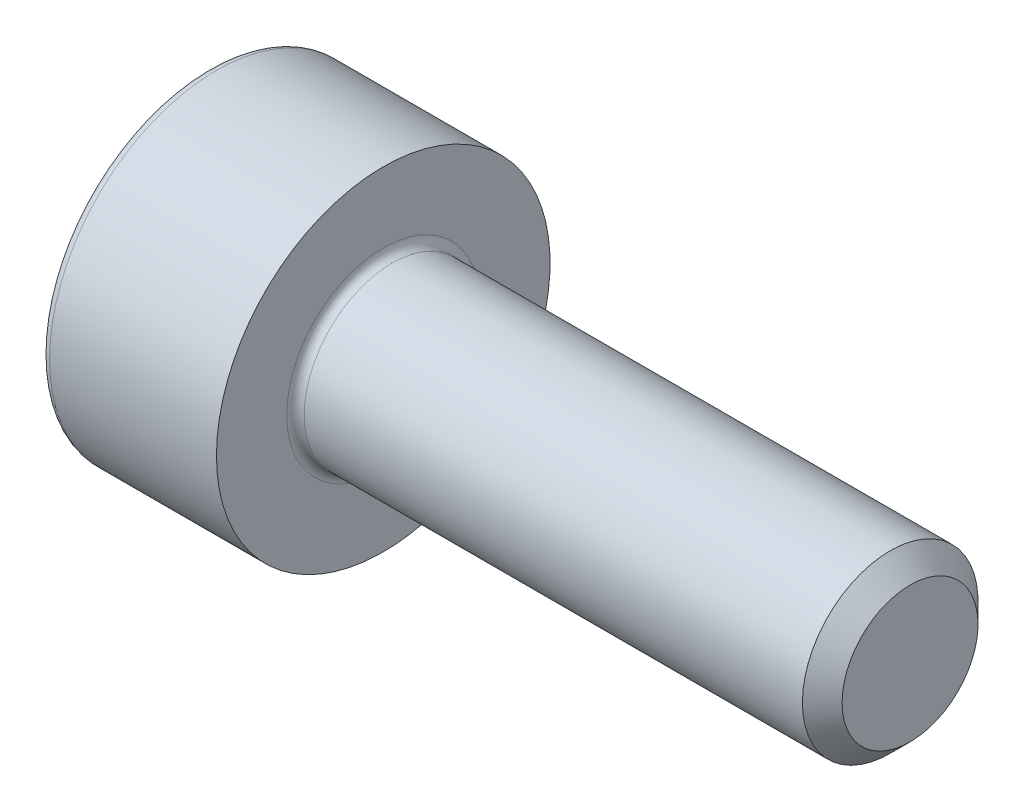
SolidWorks part; units mm, degrees
ref_plane "Plane1" through (0, 0, 0) normal (0, 0, 1) x (1, 0, 0)
ref_plane "Plane2" through (0, 0, 0) normal (0, 1, 0) x (1, 0, 0)
ref_plane "Plane3" through (0, 0, 0) normal (1, 0, 0) x (0, 0, -1)
sketch "BodySke" plane through (0, 0, 0) normal (0, 0, 1) x (1, 0, 0)
  line L0 (0, 0) -> (0, 1.9)
  line L1 (0, 1.9) -> (2, 1.9)
  line L2 (2, 1.9) -> (2, 1)
  line L3 (2, 1) -> (7.774, 1)
  line L4 (8, 0.774) -> (8, 0)
  line L5 (8, 0) -> (0, 0)
  line L6 (-31.75, 0) -> (127, 0) construction
  line L8 (8, 0.774) -> (7.774, 1)
  line L10 (8, -0.774) -> (7.774, -1) construction
  line L11 (2.4, 9.525) -> (2.4, 3.175) construction
  line L12 (2, 9.525) -> (2, 3.175) construction
  line L13 (-52, 9.525) -> (-52, 3.175) construction
  dimension "Diameter" = 2
  dimension "Head_ht" = 2
  dimension "Length" = 6
  dimension "Body_ch_ang" = 45
  dimension "Head_dia" = 3.8
  dimension "Minor_dia" = 1.548
  dimension "Advance" = 0.4
  dimension "Thread_nom" = 6
  dimension "Thread_length" = 60
revolve "Base-Revolve" add sketch "BodySke"
cosmetic thread "ThreadCosmetic" [suppressed]
fillet "Fillet1" radius 0.1 1 edges at (2, 0, 1)
fillet "Fillet2" radius 0.1 1 edges at (0, 0, 1.9)
sketch "Sketch2" plane through (0, 0, 0) normal (0, 0, 1) x (1, 0, 0)
  line L0 (0, 0.7725) -> (1, 0.7725)
  line L1 (1, 0.7725) -> (1.446, 0)
  line L2 (-31.75, 0) -> (127, 0) construction
  line L3 (1.446, 0) -> (0, 0)
  line L4 (0, 0) -> (0, 0.7725)
  line L6 (0, 0) -> (47.625, 0) construction
  dimension "D1" = 0.7725
  dimension "D2" = 60
  dimension "Depth" = 1
revolve "Hex-PreBroach" cut sketch "Sketch2" angle 360 about L6
sketch "Sketch3" plane through (0, 0, 0) normal (-1, 0, 0) x (0, 0.5, 0.866)
  line L0 (0.446, 0.7725) -> (-0.446, 0.7725)
  line L1 (-0.446, 0.7725) -> (-0.892, 0)
  line L2 (0.446, 0.7725) -> (0.892, 0)
  line L3 (0.446, -0.7725) -> (0.892, 0)
  line L4 (0.446, -0.7725) -> (-0.446, -0.7725)
  line L5 (-0.446, -0.7725) -> (-0.892, 0)
  dimension "D1" = 0.7725
  dimension "D2" = 0.7725
  dimension "Hex_size" = 1.545
extrude "Hex" cut sketch "Sketch3" against normal blind 1
sketch "ThdSchSke" plane through (0, 0, 0) normal (0, 0, 1) x (1, 0, 0)
  line L0 (3.2, -0.774) -> (3.0418, -1)
  line L1 (3.2, -0.774) -> (3.3582, -1)
  line L2 (3.3582, -1) -> (3.3582, -1.25)
  line L3 (-3.175, 0) -> (5.1513, 0) construction
  line L4 (0, 1.8) -> (0, -1.8) construction
  line L5 (3.3582, -1.25) -> (3.0418, -1.25)
  line L6 (3.0418, -1.25) -> (3.0418, -1)
  dimension "Thread_minor" = 1.548
  dimension "Diameter" = 2
  dimension "Start" = 3.2
  dimension "SideAngle" = 55
  dimension "VeeAngle" = 70
  dimension "Overcut" = 2.5
revolve "ThreadSchematic" [suppressed] cut sketch "ThdSchSke" angle 360 about L3
pattern_linear "ThdSchPat" [suppressed]
equation "\"D2@Sketch3\" = \"Hex_size@Sketch3\" / 2"
equation "\"D1@Sketch3\" = \"Hex_size@Sketch3\" / 2"
equation "\"D1@Sketch2\" = \"Hex_size@Sketch3\" / 2"
equation "\"Thread_minor@ThreadCosmetic\"  =  \"Minor_dia@BodySke\""
equation "\"Depth@Sketch2\" =  \"Key_eng@Hex\""
equation "\"Thread_length@ThreadCosmetic\" = ((sgn( (\"Length@BodySke\" - \"Advance@BodySke\" * 3.0) - \"Thread_nom@BodySke\" )-1)*( (\"Length@BodySke\" - \"Advance@BodySke\" * 3.0) - \"Thread_nom@BodySke\" ))/-2+ \"Thread_nom@BodySke\""
equation "\"Thread_minor@ThdSchSke\" = \"Minor_dia@BodySke\""
equation "\"Diameter@ThdSchSke\" = \"Diameter@BodySke\""
equation "\"Overcut@ThdSchSke\" = \"Diameter@BodySke\" * 1.25"
equation "\"Start@ThdSchSke\" = \"Head_ht@BodySke\" + \"Length@BodySke\" - \"Thread_length@ThreadCosmetic\"  '---Non-countersunk---"
equation "\"Num_threads@ThdSchPat\" = int( \"Thread_length@ThreadCosmetic\" / \"Advance@BodySke\" + 0.999 )  + 1"
equation "\"Advance@ThdSchPat\" = \"Thread_length@ThreadCosmetic\" /  (\"Num_threads@ThdSchPat\" - 1) 'relax it"
equation "\"Num_threads@ThdSchPat\" = \"Num_threads@ThdSchPat\" - sgn( \"Num_threads@ThdSchPat\" - 1) '---chamfered tips only---"
